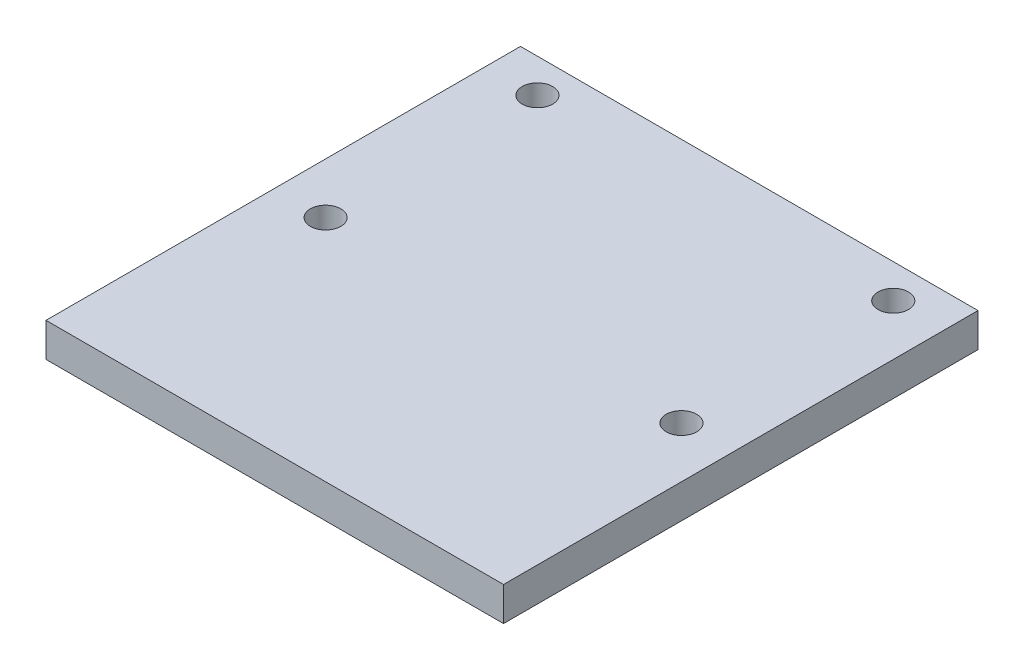
SolidWorks part; units mm, degrees
ref_plane "Front Plane" through (0, 0, 0) normal (0, 0, 1) x (1, 0, 0)
ref_plane "Top Plane" through (0, 0, 0) normal (0, 1, 0) x (1, 0, 0)
ref_plane "Right Plane" through (0, 0, 0) normal (1, 0, 0) x (0, 0, -1)
sketch "Sketch3" plane through (0, 0, 0) normal (0, 1, 0) x (1, 0, 0)
  line L1 (-13.5, 0) -> (13.5, 0)
  line L2 (-13.5, 0) -> (-13.5, -28)
  line L3 (-13.5, -28) -> (13.5, -28)
  line L4 (13.5, 0) -> (13.5, -28)
  dimension "D1" = 27
  dimension "D2" = 28
extrude "Boss-Extrude1" add sketch "Sketch3" against normal blind 2
sketch "Sketch2" plane through (0, 0, 0) normal (0, 1, 0) x (1, 0, 0)
  line L0 (0, 0) -> (0, -28) construction
  line L1 (-13.5, -28) -> (13.5, -28) construction
  line L2 (13.5, 0) -> (-13.5, 0) construction
  line L3 (-13.5, 0) -> (-13.5, -28) construction
  circle A0 centre (-10.5, -2) radius 0.9
  circle A1 centre (-10.5, -14.5) radius 0.9
  circle A2 centre (10.5, -14.5) radius 0.9
  circle A3 centre (10.5, -2) radius 0.9
  dimension "D1" = 1.8
  dimension "D2" = 1.8
  dimension "D4" = 10.5
  dimension "D5" = 2
  dimension "D6" = 3
  dimension "D3" = 12.5
extrude "Cut-Extrude1" cut sketch "Sketch2" against normal blind 10
